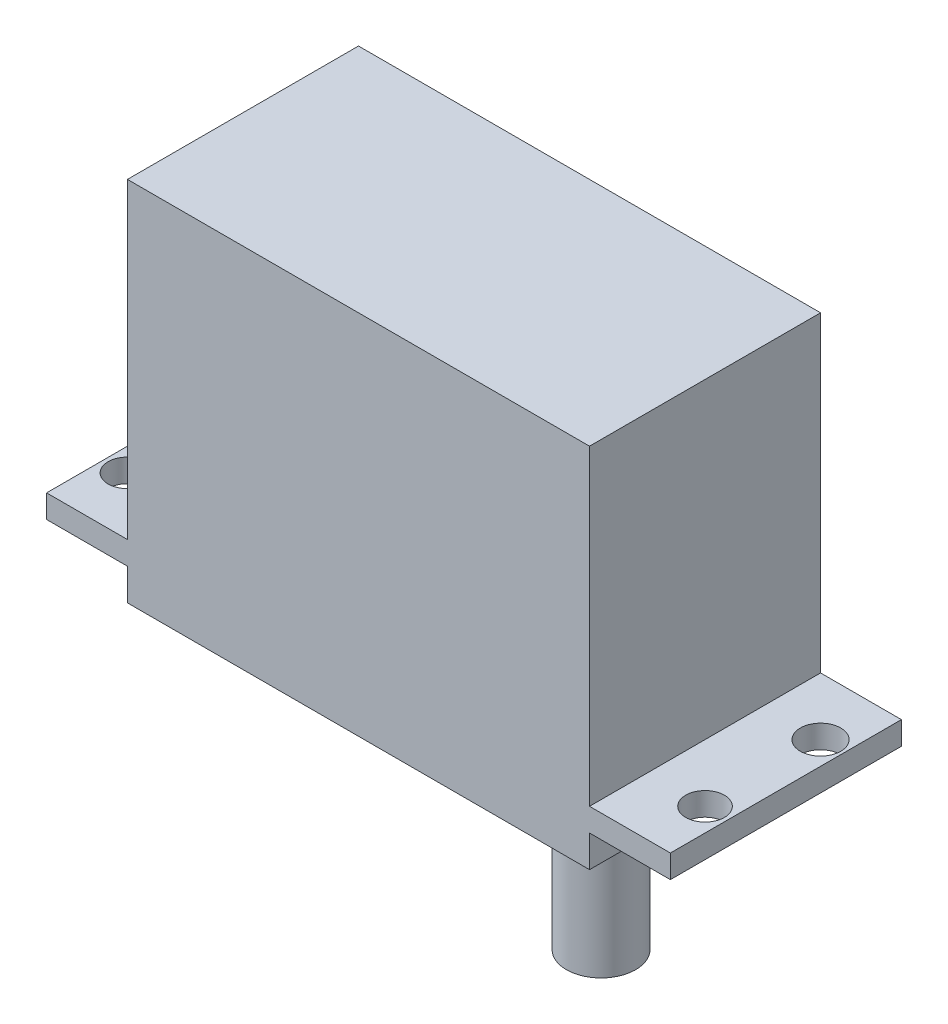
SolidWorks part; units mm, degrees
ref_plane "Front Plane" through (0, 0, 0) normal (0, 0, 1) x (1, 0, 0)
ref_plane "Top Plane" through (0, 0, 0) normal (0, 1, 0) x (1, 0, 0)
ref_plane "Right Plane" through (0, 0, 0) normal (1, 0, 0) x (0, 0, -1)
sketch "Sketch1" plane through (0, 0, 0) normal (0, 1, 0) x (1, 0, 0)
  line L1 (-17.8039, 11.0588) -> (22.1961, 11.0588)
  line L2 (-17.8039, 11.0588) -> (-17.8039, -8.9412)
  line L3 (-17.8039, -8.9412) -> (22.1961, -8.9412)
  line L4 (22.1961, 11.0588) -> (22.1961, -8.9412)
  dimension "D1" = 40
  dimension "D2" = 20
extrude "Boss-Extrude1" add sketch "Sketch1" along normal mid plane 28
sketch "Sketch2" plane through (0, -14, 0) normal (0, -1, 0) x (1, 0, 0)
  line L0 (-17.8039, 8.9412) -> (22.1961, 8.9412) construction
  line L1 (-24.8039, 8.9412) -> (29.1961, 8.9412)
  line L2 (-24.8039, 8.9412) -> (-24.8039, -11.0588)
  line L3 (-24.8039, -11.0588) -> (29.1961, -11.0588)
  line L4 (29.1961, 8.9412) -> (29.1961, -11.0588)
  line L5 (-17.8039, -11.0588) -> (-17.8039, 8.9412) construction
  dimension "D1" = 54
  dimension "D2" = 20
  dimension "D3" = 7
extrude "Boss-Extrude2" add sketch "Sketch2" along normal mid plane 2
sketch "Sketch3" plane through (0, -15, 0) normal (0, -1, 0) x (1, 0, 0)
  line L1 (-17.8039, 8.9412) -> (22.1961, 8.9412)
  line L2 (-17.8039, 8.9412) -> (-17.8039, -11.0588)
  line L3 (-17.8039, -11.0588) -> (22.1961, -11.0588)
  line L4 (22.1961, 8.9412) -> (22.1961, -11.0588)
  line L5 (29.1961, 8.9412) -> (-24.8039, 8.9412) construction
  line L6 (29.1961, -11.0588) -> (29.1961, 8.9412) construction
  dimension "D1" = 40
  dimension "D2" = 20
  dimension "D3" = 7
extrude "Boss-Extrude3" add sketch "Sketch3" along normal mid plane 5.5
sketch "Sketch4" plane through (0, -17.75, 0) normal (0, -1, 0) x (1, 0, 0)
  line L0 (-17.8039, -11.0588) -> (22.1961, -11.0588) construction
  line L1 (29.1961, -11.0588) -> (29.1961, 8.9412) construction
  circle A0 centre (13.1961, -1.0588) radius 3
  dimension "D1" = 6
  dimension "D2" = 10
  dimension "D3" = 16
extrude "Boss-Extrude4" add sketch "Sketch4" along normal mid plane 31
sketch "Sketch5" plane through (0, -15, 0) normal (0, -1, 0) x (1, 0, 0)
  line L2 (-24.8039, -11.0588) -> (-17.8039, -11.0588) construction
  line L4 (-24.8039, 8.9412) -> (-24.8039, -11.0588) construction
  circle A4 centre (-22.8039, 3.9412) radius 1.6736
  circle A5 centre (-22.8039, -6.0588) radius 1.7494
  dimension "D1" = 10
  dimension "D2" = 5
  dimension "D10" = 2
  dimension "D9" = 2
extrude "Cut-Extrude3" cut sketch "Sketch5" against normal blind 9.5
ref_plane "Plane1" through (2.1961, 0, 0) normal (-1, 0, 0) x (0, 0, 1)
mirror "Mirror1" about plane through (2.1961, 0, 0) normal (-1, 0, 0) of "Cut-Extrude3"
